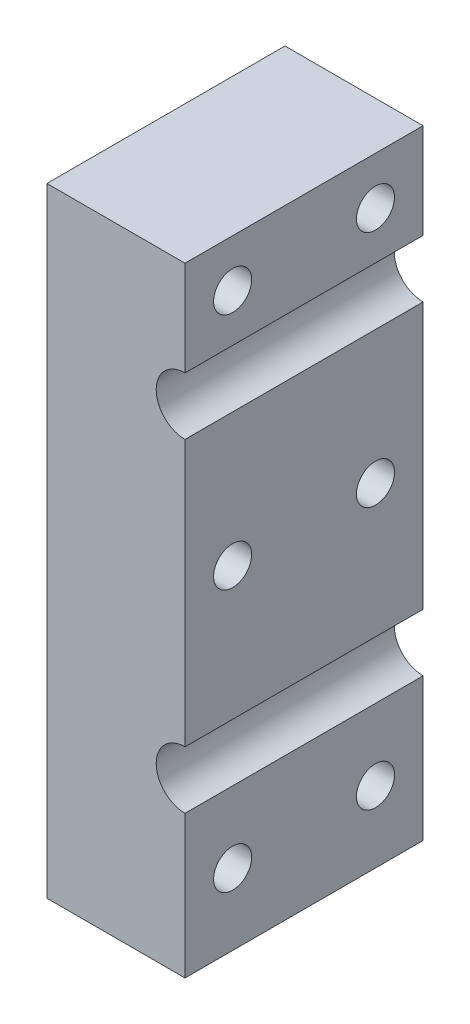
SolidWorks part; units mm, degrees
ref_plane "前视基准面" through (0, 0, 0) normal (0, 0, 1) x (1, 0, 0)
ref_plane "上视基准面" through (0, 0, 0) normal (0, 1, 0) x (1, 0, 0)
ref_plane "右视基准面" through (0, 0, 0) normal (1, 0, 0) x (0, 0, -1)
sketch "草图1" plane through (0, 0, 0) normal (0, 0, 1) x (1, 0, 0)
  line L1 (0, 0) -> (29, 0)
  line L2 (0, 0) -> (0, 65)
  line L3 (0, 65) -> (29, 65)
  line L4 (29, 0) -> (29, 65)
extrude "凸台-拉伸1" add sketch "草图1" along normal blind 25
sketch "草图2" plane through (0, 0, 25) normal (0, 0, 1) x (1, 0, 0)
  line L0 (0, 0) -> (29, 0) construction
  circle A0 centre (14.5, 52) radius 3.005
  circle A1 centre (14.5, 18) radius 3.005
  circle A2 centre (14.5, 52) radius 3.025
  circle A3 centre (14.5, 18) radius 3.025
  dimension "D1" = 0.02
  dimension "D2" = 34
  dimension "D3" = 18
extrude "切除-拉伸3" cut sketch "草图2" against normal through all
sketch "草图6" plane through (0, 0, 25) normal (0, 0, 1) x (1, 0, 0)
  line L0 (29, 65) -> (0, 65) construction
  line L1 (14.5, 65) -> (29, 65)
  line L2 (14.5, 65) -> (14.5, 0)
  line L3 (14.5, 0) -> (29, 0)
  line L4 (29, 65) -> (29, 0)
extrude "切除-拉伸4" cut sketch "草图6" against normal through all
sketch "草图7" plane through (14.5, 0, 0) normal (1, 0, 0) x (0, 0, -1)
  line L0 (-25, 65) -> (-25, 55.025) construction
  circle A0 centre (-20, 60.0125) radius 2
  circle A2 centre (-5, 60.0125) radius 2
  point P2 (0, 0)
  dimension "D1" = 4
  dimension "D3" = 15
  dimension "D2" = 5
extrude "切除-拉伸5" cut sketch "草图7" against normal through all
sketch "草图8" plane through (14.5, 0, 0) normal (1, 0, 0) x (0, 0, -1)
  line L0 (-25, 48.975) -> (-25, 21.025) construction
  circle A0 centre (-20, 35) radius 2
  circle A3 centre (-5, 35) radius 2
  dimension "D2" = 15
  dimension "D3" = 4
  dimension "D1" = 5
extrude "切除-拉伸6" cut sketch "草图8" against normal through all
sketch "草图9" plane through (14.5, 0, 0) normal (1, 0, 0) x (0, 0, -1)
  line L0 (-25, 14.975) -> (-25, 0) construction
  circle A0 centre (-20, 7.4875) radius 2
  circle A3 centre (-5, 7.4875) radius 2
  dimension "D5" = 4
  dimension "D2" = 15
  dimension "D1" = 5
extrude "切除-拉伸7" cut sketch "草图9" against normal through all
